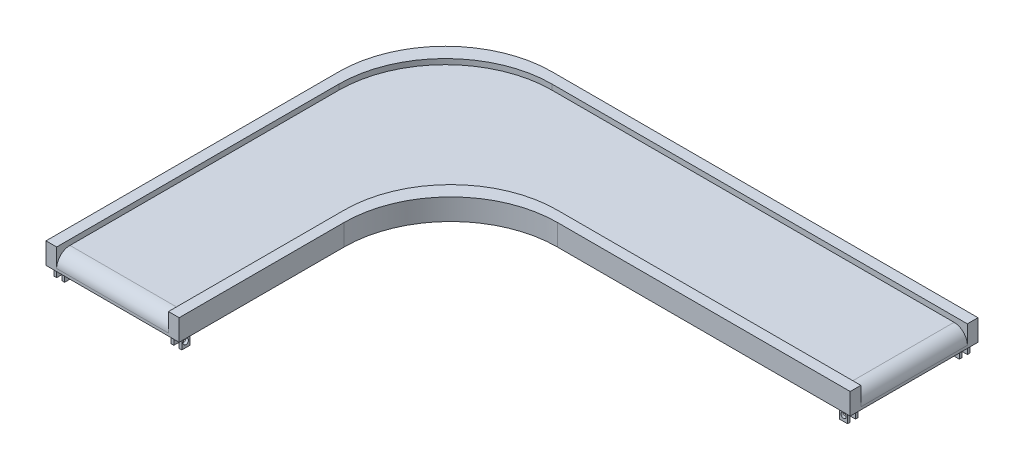
SolidWorks part; units mm, degrees
ref_plane "Front Plane" through (0, 0, 0) normal (0, 0, 1) x (1, 0, 0)
ref_plane "Top Plane" through (0, 0, 0) normal (0, 1, 0) x (1, 0, 0)
ref_plane "Right Plane" through (0, 0, 0) normal (1, 0, 0) x (0, 0, -1)
sketch "Sketch1" plane through (0, 0, 0) normal (0, 1, 0) x (1, 0, 0)
  line L0 (1016, 0) -> (5080, 0)
  line L1 (5080, 0) -> (5080, -1219.2)
  line L2 (5080, -1219.2) -> (2286, -1219.2)
  line L3 (0, -1016) -> (0, -3810)
  line L4 (0, -3810) -> (1270, -3810)
  line L5 (1270, -3810) -> (1270, -2235.2)
  arc A0 (2286, -1219.2) -> (1270, -2235.2) centre (2286, -2235.2) ccw
  arc A1 (1016, 0) -> (0, -1016) centre (1016, -1016) ccw
  point P11 (0, 0)
  dimension "D1" = 1016
extrude "Boss-Extrude1" add sketch "Sketch1" along normal blind 203.2
sketch "Sketch2" plane through (0, 203.2, 0) normal (0, 1, 0) x (1, 0, 0)
  line L0 (0, -3810) -> (101.6, -3810)
  line L1 (0, -3810) -> (1270, -3810) construction
  line L2 (101.6, -3810) -> (101.6, -1117.6)
  line L3 (1117.6, -101.6) -> (5080, -101.6)
  line L4 (5080, -1219.2) -> (5080, 0) construction
  line L5 (5080, -1219.2) -> (5080, -1117.6)
  line L6 (5080, -1117.6) -> (2184.4, -1117.6)
  line L7 (1168.4, -2133.6) -> (1168.4, -3810)
  line L8 (5080, -101.6) -> (5080, -1117.6)
  line L9 (1168.4, -3810) -> (101.6, -3810)
  arc A0 (2184.4, -1117.6) -> (1168.4, -2133.6) centre (2184.4, -2133.6) ccw
  arc A1 (101.6, -1117.6) -> (1117.6, -101.6) centre (1117.6, -1117.6) cw
  line M2 (5080, -1219.2) -> (5080, 0)
  line M6 (0, -3810) -> (1270, -3810)
  dimension "D1" = 1016
extrude "Cut-Extrude1" cut sketch "Sketch2" against normal blind 50.8 contours A1 L2 L7 A0 L6 L3 M6 M2
fillet "Fillet1" radius 127 2 edges at (5080, 152.4, 609.6) (635, 152.4, 3810)
sketch "Sketch3" plane through (0, 0, 0) normal (0, -1, 0) x (-1, 0, 0)
  line L0 (0, -3810) -> (-127, -3810)
  line L1 (0, -3810) -> (-1270, -3810) construction
  line L2 (-127, -3810) -> (-127, -3683)
  line L3 (-127, -3683) -> (-101.6, -3683)
  line L4 (-101.6, -3683) -> (-101.6, -3759.2)
  line L5 (-101.6, -3759.2) -> (-127, -3759.2)
  line L6 (-127, -3759.2) -> (-50.8, -3759.2)
  line L7 (-50.8, -3759.2) -> (-50.8, -3683)
  line L8 (-50.8, -3683) -> (-26.1023, -3683)
  line L9 (-26.1023, -3683) -> (-26.1023, -3759.2)
  line L10 (-26.1023, -3759.2) -> (-50.8, -3759.2)
  line L11 (-1270, -3810) -> (-1143, -3810)
  line L12 (-1143, -3810) -> (-1143, -3683)
  line L13 (-1143, -3683) -> (-1168.4, -3683)
  line L14 (-1168.4, -3683) -> (-1168.4, -3759.2)
  line L15 (-1168.4, -3759.2) -> (-1143, -3759.2)
  line L16 (-1143, -3759.2) -> (-1219.2, -3759.2)
  line L17 (-1219.2, -3759.2) -> (-1219.2, -3683)
  line L18 (-1219.2, -3683) -> (-1244.6, -3683)
  line L19 (-1244.6, -3683) -> (-1244.6, -3759.2)
  line L20 (-1244.6, -3759.2) -> (-1219.2, -3759.2)
  line L21 (-5080, -1219.2) -> (-5080, -1092.2)
  line L22 (-5080, -1219.2) -> (-5080, 0) construction
  line L23 (-5080, -1092.2) -> (-4953, -1092.2)
  line L24 (-4953, -1092.2) -> (-4953, -1168.4)
  line L25 (-4953, -1168.4) -> (-5029.2, -1168.4)
  line L26 (-5029.2, -1168.4) -> (-5029.2, -1193.8)
  line L27 (-5029.2, -1193.8) -> (-4953, -1193.8)
  line L28 (-4953, -1193.8) -> (-4953, -1168.4)
  line L29 (-5029.2, -1092.2) -> (-5029.2, -1117.6)
  line L30 (-5029.2, -1117.6) -> (-4953, -1117.6)
  line L31 (-5080, 0) -> (-5080, -127)
  line L32 (-5080, -127) -> (-4953, -127)
  line L33 (-4953, -127) -> (-4953, -101.6)
  line L34 (-4953, -101.6) -> (-5029.2, -101.6)
  line L35 (-5029.2, -101.6) -> (-5029.2, -127)
  line L36 (-5029.2, -127) -> (-5029.2, -50.8)
  line L37 (-5029.2, -50.8) -> (-4953, -50.8)
  line L38 (-4953, -50.8) -> (-4953, -25.4)
  line L39 (-4953, -25.4) -> (-5029.2, -25.4)
  line L40 (-5029.2, -25.4) -> (-5029.2, -50.8)
extrude "Boss-Extrude2" add sketch "Sketch3" along normal blind 101.6 contours L39 L40 L37 L38 | L34 L35 L32 L33 | L29 L30 L24 L23 | L27 L28 L25 L26 | L10 L9 L8 L7 | L5 L4 L3 L2 | L19 L20 L17 L18 | L14 L15 L12 L13
sketch "Sketch4" plane through (26.1023, 0, 0) normal (-1, 0, 0) x (0, 0, 1)
  line L0 (3721.1, 0) -> (3721.1, -50.8)
  line L1 (3683, 0) -> (3759.2, 0) construction
  circle A0 centre (3721.1, -50.8) radius 25.4
extrude "Cut-Extrude2" cut sketch "Sketch4" against normal blind 1270
sketch "Sketch5" plane through (0, 0, 25.4) normal (0, 0, -1) x (-1, 0, 0)
  line L0 (-4991.1, -101.6) -> (-4991.1, -50.8)
  line L2 (-4953, -101.6) -> (-5029.2, -101.6) construction
  circle A0 centre (-4991.1, -50.8) radius 25.4
extrude "Cut-Extrude3" cut sketch "Sketch5" against normal blind 1270
